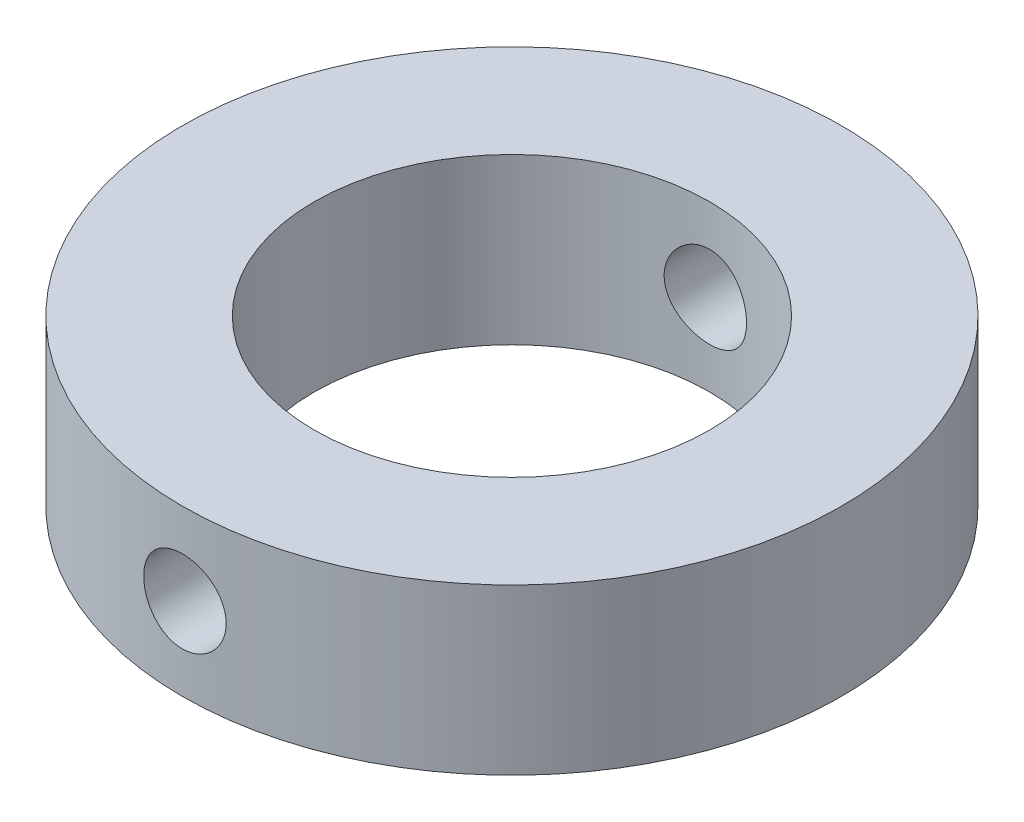
SolidWorks part; units mm, degrees
ref_plane "Front Plane" through (0, 0, 0) normal (0, 0, 1) x (1, 0, 0)
ref_plane "Top Plane" through (0, 0, 0) normal (0, 1, 0) x (1, 0, 0)
ref_plane "Right Plane" through (0, 0, 0) normal (1, 0, 0) x (0, 0, -1)
sketch "Sketch1" plane through (0, 0, 0) normal (0, 1, 0) x (1, 0, 0)
  circle A0 centre (0, 0) radius 6
  circle A1 centre (0, 0) radius 10
  dimension "D1" = 12
  dimension "D2" = 20
extrude "Boss-Extrude1" add sketch "Sketch1" along normal blind 5
sketch "Sketch2" plane through (0, 0, 0) normal (0, 0, 1) x (1, 0, 0)
  line L0 (10, 0) -> (10, 5) construction
  circle A0 centre (0, 2.5) radius 1.25
  dimension "D2" = 2.5
  dimension "D1" = 2.5
  dimension "D3" = 10
extrude "Cut-Extrude1" cut sketch "Sketch2" against normal through all both and the other way through all
